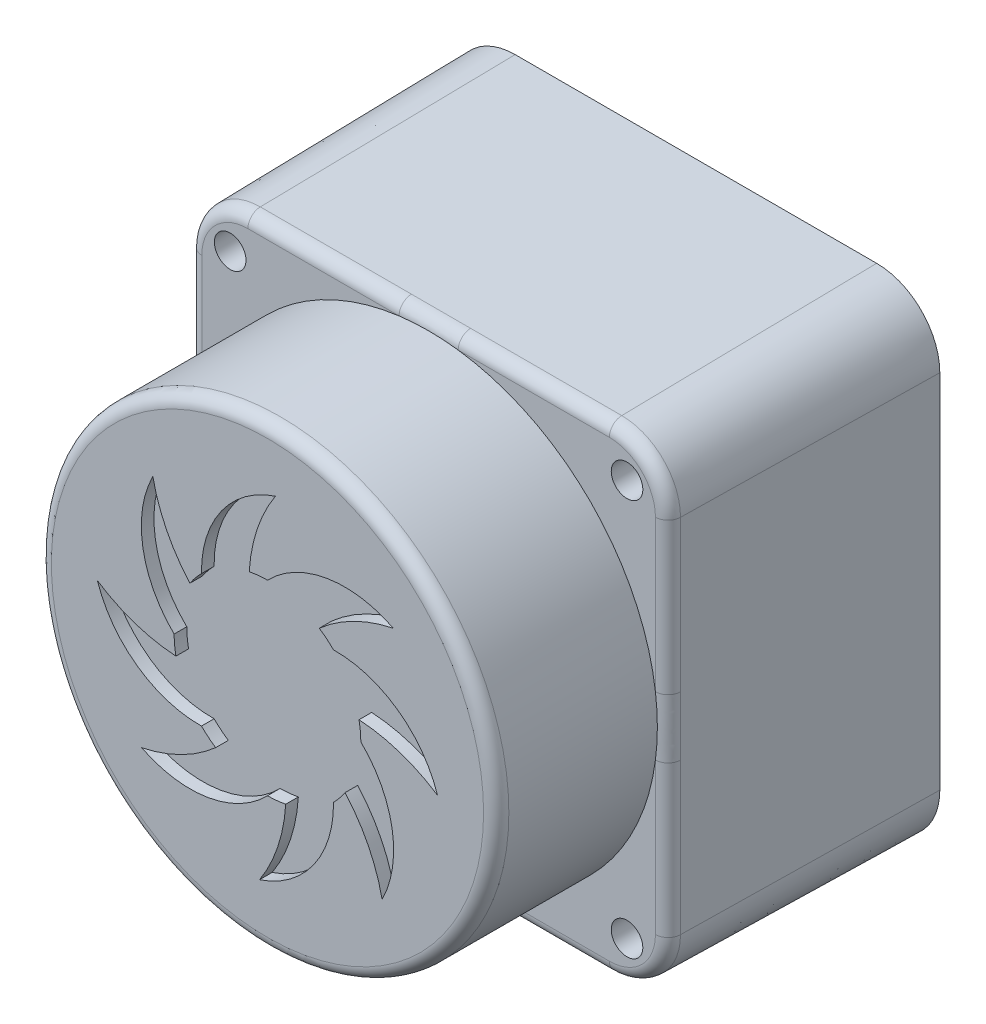
SolidWorks part; units mm, degrees
ref_plane "Front Plane" through (0, 0, 0) normal (0, 0, 1) x (1, 0, 0)
ref_plane "Top Plane" through (0, 0, 0) normal (0, 1, 0) x (1, 0, 0)
ref_plane "Right Plane" through (0, 0, 0) normal (1, 0, 0) x (0, 0, -1)
sketch "Sketch1" plane through (0, 0, 0) normal (0, 0, 1) x (1, 0, 0)
  line L1 (-14.3, 19.3) -> (14.3, 19.3)
  line L2 (-19.3, 14.3) -> (-19.3, -14.3)
  line L3 (-14.3, -19.3) -> (14.3, -19.3)
  line L4 (19.3, 14.3) -> (19.3, -14.3)
  line L5 (-19.3, 19.3) -> (19.3, -19.3) construction
  line L6 (-19.3, -19.3) -> (19.3, 19.3) construction
  arc A0 (-19.3, -14.3) -> (-14.3, -19.3) centre (-14.3, -14.3) ccw
  arc A1 (14.3, -19.3) -> (19.3, -14.3) centre (14.3, -14.3) ccw
  arc A2 (14.3, 19.3) -> (19.3, 14.3) centre (14.3, 14.3) cw
  arc A3 (-14.3, 19.3) -> (-19.3, 14.3) centre (-14.3, 14.3) ccw
  point P0 (0, 0)
  dimension "D2" = 5
  dimension "D1" = 38.6
extrude "Boss-Extrude1" add sketch "Sketch1" along normal blind 21.15 draft 1
sketch "Sketch2" plane through (0, 0, 21.15) normal (0, 0, 1) x (1, 0, 0)
  circle A0 centre (0, 0) radius 18.1
  dimension "D1" = 36.2
extrude "Boss-Extrude2" add sketch "Sketch2" along normal blind 12.75
sketch "Sketch3" plane through (0, 0, 21.15) normal (0, 0, 1) x (1, 0, 0)
  line L0 (0, -18.645) -> (0, 18.645) construction
  line L1 (18.645, 0) -> (-18.645, 0) construction
  circle A0 centre (-15.7, 15.7) radius 1.25
  circle A1 centre (15.7, 15.7) radius 1.25
  circle A2 centre (15.7, -15.7) radius 1.25
  circle A3 centre (-15.7, -15.7) radius 1.25
  dimension "D3" = 2.5
  dimension "D1" = 15.7
  dimension "D2" = 15.7
extrude "Cut-Extrude1" cut sketch "Sketch3" against normal through all
fillet "Fillet1" radius 1 9 edges at (-17.5745, -17.5745, 21.15) (-18.9308, 0, 21.15) (-17.5745, 17.5745, 21.15) (0, 18.9308, 21.15) (17.5745, 17.5745, 21.15) (18.9308, 0, 21.15) (17.5745, -17.5745, 21.15) (0, -18.9308, 21.15) (18.1, 0, 33.9)
sketch "Sketch4" plane through (0, 0, 33.9) normal (0, 0, 1) x (1, 0, 0)
  arc A0 (0, 7.386) -> (4.1006, 6.1431) centre (0, 0) ccw
  arc A1 (0, 7.386) -> (9.9586, 9.0706) centre (6.1241, 1.4608) cw
  arc A2 (9.9586, 9.0706) -> (4.1006, 6.1431) centre (12.5364, -3.4122) ccw
  point P1 (9.9596, 9.0726)
  point P8 (0, 7.3966)
  point P9 (5.9063, 10.5708)
  point P10 (4.1006, 6.1431)
extrude "Cut-Extrude2" cut sketch "Sketch4" against normal blind 1
pattern_circular "CirPattern1" count 8 over 360 about axis through (0, 0, 0) along (0, 0, 1) of "Cut-Extrude2"
